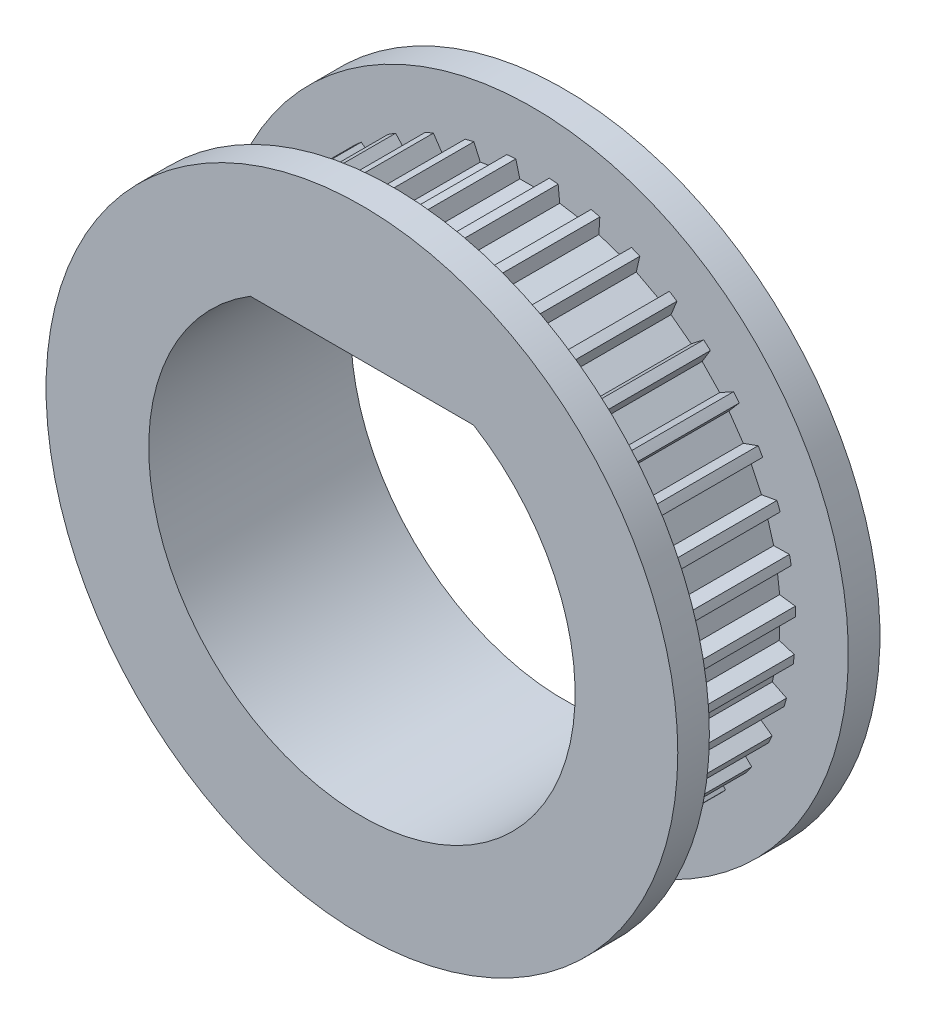
SolidWorks part; units mm, degrees
ref_plane "Front Plane" through (0, 0, 0) normal (0, 0, 1) x (1, 0, 0)
ref_plane "Top Plane" through (0, 0, 0) normal (0, 1, 0) x (1, 0, 0)
ref_plane "Right Plane" through (0, 0, 0) normal (1, 0, 0) x (0, 0, -1)
sketch "Sketch1" plane through (0, 0, 0) normal (0, 0, 1) x (1, 0, 0)
  circle A0 centre (0, 0) radius 12.5
  dimension "D1" = 25
extrude "Boss-Extrude1" add sketch "Sketch1" along normal mid plane 6.6
sketch "Sketch3" plane through (0, 0, 3.3) normal (0, 0, 1) x (1, 0, 0)
  circle A0 centre (0, 0) radius 15
  dimension "D1" = 30
sketch "Sketch2" plane through (0, 0, -3.3) normal (0, 0, -1) x (-1, 0, 0)
  circle A0 centre (0, 0) radius 15
  dimension "D1" = 30
sketch "Sketch4" plane through (0, 0, 3.3) normal (0, 0, 1) x (1, 0, 0)
  line L0 (-0.6, 11.75) -> (0.6, 11.75)
  line L1 (0.6, 11.75) -> (0.8, 12.5)
  line L2 (0.8, 12.5) -> (-0.8, 12.5)
  line L3 (-0.8, 12.5) -> (-0.6, 11.75)
  circle A0 centre (0, 0) radius 12.5 construction
  point P10 (0, 11.75)
  dimension "D1" = 1.2
  dimension "D2" = 1.6
  dimension "D3" = 0.75
extrude "Cut-Extrude1" cut sketch "Sketch4" against normal up to surface (6.6 mm away) and the other way through all up to face at (12.5, 0, -3.3)
pattern_circular "CirPattern2" count 39 over 360 about axis through (0, 0, 0) along (0, 0, 1) of "Cut-Extrude1"
extrude "Boss-Extrude3" add sketch "Sketch2" along normal blind 1.5
extrude "Boss-Extrude4" add sketch "Sketch3" along normal blind 1.5 contours A0
sketch "Sketch6" plane through (0, 0, 4.8) normal (0, 0, 1) x (1, 0, 0)
  line L0 (-5.3033, 8.625) -> (5.3033, 8.625)
  circle A0 centre (0, 0) radius 10.125
  point P5 (0, 10.125)
  dimension "D1" = 20.25
  dimension "D2" = 1.5
extrude "Cut-Extrude3" cut sketch "Sketch6" against normal through all both and the other way through all contours L0 A0
